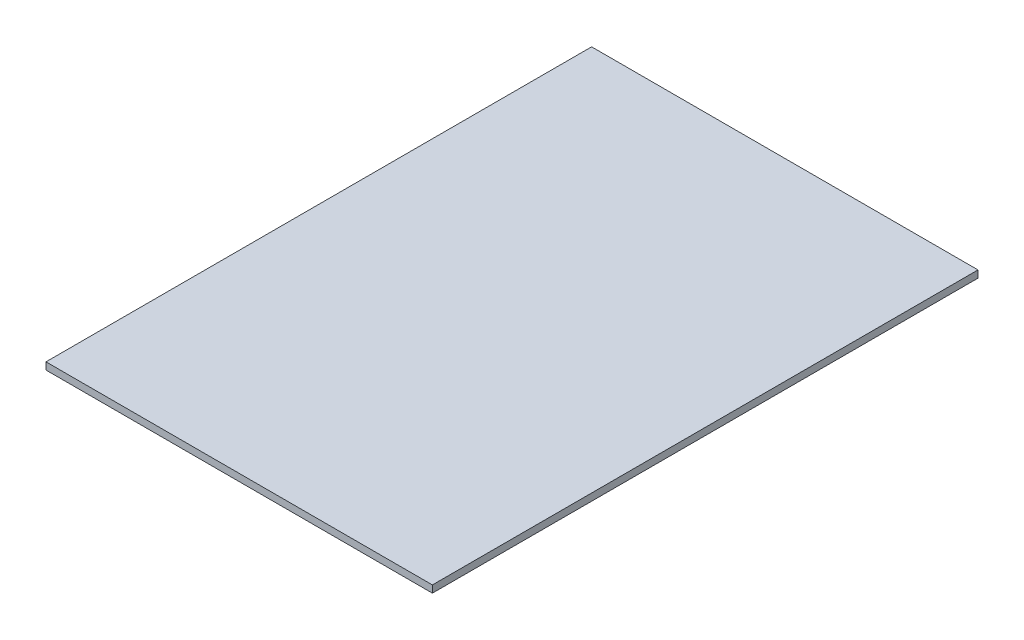
SolidWorks part; units mm, degrees
ref_plane "Alzado" through (0, 0, 0) normal (0, 0, 1) x (1, 0, 0)
ref_plane "Planta" through (0, 0, 0) normal (0, 1, 0) x (1, 0, 0)
ref_plane "Vista lateral" through (0, 0, 0) normal (1, 0, 0) x (0, 0, -1)
sketch "Croquis1" plane through (0, 0, 0) normal (0, 1, 0) x (1, 0, 0)
  line L1 (108, 155) -> (-108, 155)
  line L2 (108, 155) -> (108, -155)
  line L3 (108, -155) -> (-108, -155)
  line L4 (-108, 155) -> (-108, -155)
  line L5 (108, 155) -> (-108, -155) construction
  line L6 (108, -155) -> (-108, 155) construction
  point P0 (0, 0)
  dimension "D1" = 216
  dimension "D2" = 310
extrude "Saliente-Extruir1" add sketch "Croquis1" along normal blind 4
sketch "Croquis2" plane through (0, 4, 0) normal (0, 1, 0) x (1, 0, 0)
  line L5 (108, -155) -> (108, 155) construction
  line L6 (-108, 155) -> (108, 155)
  line L12 (-108, 155) -> (-108, 152.5)
  line L13 (-108, 152.5) -> (108, 152.5)
  line L18 (108, 155) -> (108, 152.5)
  line L19 (-108, 155) -> (108, 152.5) construction
  line L20 (-108, 152.5) -> (108, 155) construction
  line L26 (-108, -155) -> (108, -155)
  line L27 (-108, -155) -> (-108, -152.5)
  line L28 (-108, -152.5) -> (108, -152.5)
  line L29 (108, -155) -> (108, -152.5)
  line L30 (-108, -155) -> (108, -152.5) construction
  line L31 (-108, -152.5) -> (108, -155) construction
  point P4 (0, 153.75)
  point P11 (0, -153.75)
  dimension "D1" = 2.5
extrude "Cortar-Extruir1" cut sketch "Croquis2" against normal blind 4
equation "\"venesta\"= 4'grosor de la venesta"
equation "\"policarbonato\"= 4'grosor del policarbonato"
equation "\"carton_trupan\"= 3'grosor del carton trupan caso laser"
equation "\"ancho_tot\"= 310'ancho tot sin llantas"
equation "\"largo_tot\"= 400'largo tot sin camera"
equation "\"alto_estimado\"= 300'alto estimado sin lidar"
equation "\"altoparaqpaselabotella\"= 75'alto estimado para que encaje la botella"
equation "\"alturaruedaloca\"= 22"
equation "\"anchoruedaloca\"= 35"
equation "\"anchopiso1motorybaterias\"= 150"
equation "\"dist-pisorampa\"= 5"
equation "\"anchoultimopiso\"= 170"
equation "\"paredtrasera\"= 100"
equation "\"agarradorcanasta\"= 275'recolector"
equation "\"alturapiso1y2\"= 80"
equation "\"alturapiso2y3\"= 80"
equation "\"D2@Croquis1\"=\"ancho_tot\""
equation "\"D1@Saliente-Extruir1\"=\"venesta\""
equation "\"TOLERANCIA\"= 0.05"
equation "\"GROSOR_PARED_IMPRESION\"= 2.5"
equation "\"D1@Croquis2\"=\"GROSOR_PARED_IMPRESION\""
